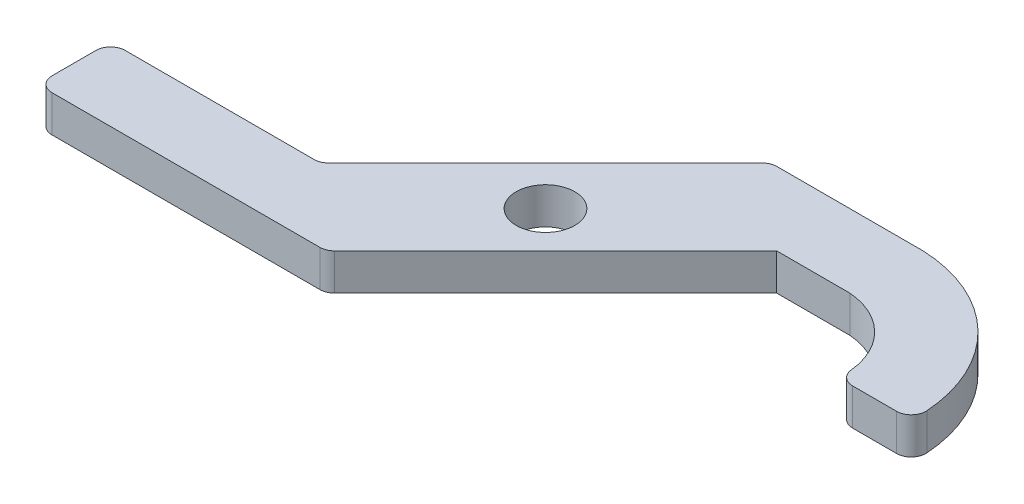
SolidWorks part; units mm, degrees
ref_plane "Front Plane" through (0, 0, 0) normal (0, 0, 1) x (1, 0, 0)
ref_plane "Top Plane" through (0, 0, 0) normal (0, 1, 0) x (1, 0, 0)
ref_plane "Right Plane" through (0, 0, 0) normal (1, 0, 0) x (0, 0, -1)
sketch "Sketch1" plane through (0, 0, 0) normal (0, 1, 0) x (1, 0, 0)
  line L0 (0, 24.73) -> (0, 38.3745)
  line L1 (0, 11.9706) -> (0, -0.7294)
  line L2 (-11.9561, 0.0739) -> (26.4039, 38.4339)
  line L3 (0, 24.73) -> (0, 11.9706)
  line L5 (0, 11.9706) -> (33.0186, 11.9706) construction
  line L6 (-25.6599, 12.7739) -> (11.9561, 50.3899)
  line L9 (-13.7521, -0.67) -> (-60.2306, -0.67)
  line L10 (-62.7706, 1.87) -> (-62.7706, 9.49)
  line L11 (-27.456, 12.03) -> (-60.2306, 12.03)
  line L12 (0, 38.3745) -> (0, 51.0745) construction
  line L14 (0, 24.73) -> (63.5, 24.73) construction
  line L16 (26.4039, 38.4339) -> (39.1039, 38.4339)
  line L17 (13.7521, 51.1339) -> (39.1039, 51.1339)
  line L18 (53.3022, 24.73) -> (60.9282, 24.73)
  circle A0 centre (0, 24.73) radius 5.08
  arc A1 (39.1039, 38.4339) -> (50.7751, 27.0146) centre (38.1, 25.7339) cw
  arc A2 (39.1039, 51.1339) -> (63.4625, 27.4405) centre (38.1, 25.7339) cw
  arc A3 (60.9282, 24.73) -> (63.4625, 27.4405) centre (60.9282, 27.27) ccw
  arc A4 (53.3022, 24.73) -> (50.7751, 27.0146) centre (53.3022, 27.27) cw
  arc A5 (-60.2306, 12.03) -> (-62.7706, 9.49) centre (-60.2306, 9.49) ccw
  arc A6 (-60.2306, -0.67) -> (-62.7706, 1.87) centre (-60.2306, 1.87) cw
  arc A7 (-11.9561, 0.0739) -> (-13.7521, -0.67) centre (-13.7521, 1.87) cw
  arc A8 (-25.6599, 12.7739) -> (-27.456, 12.03) centre (-27.456, 14.57) cw
  arc A9 (11.9561, 50.3899) -> (13.7521, 51.1339) centre (13.7521, 48.5939) cw
  point P6 (0, 0)
  point P26 (50.8, 24.73)
  point P35 (0, 0)
  point P38 (0, 0)
  dimension "D1" = 10.16
  dimension "D2" = 2.54
  dimension "D3" = 2.54
extrude "Boss-Extrude1" add sketch "Sketch1" along normal blind 6.35 contours L6 A9 L17 A2 A3 L18 A4 A1 L16 L2 A7 L9 A6 L10 A5 L11 A8 | A0
